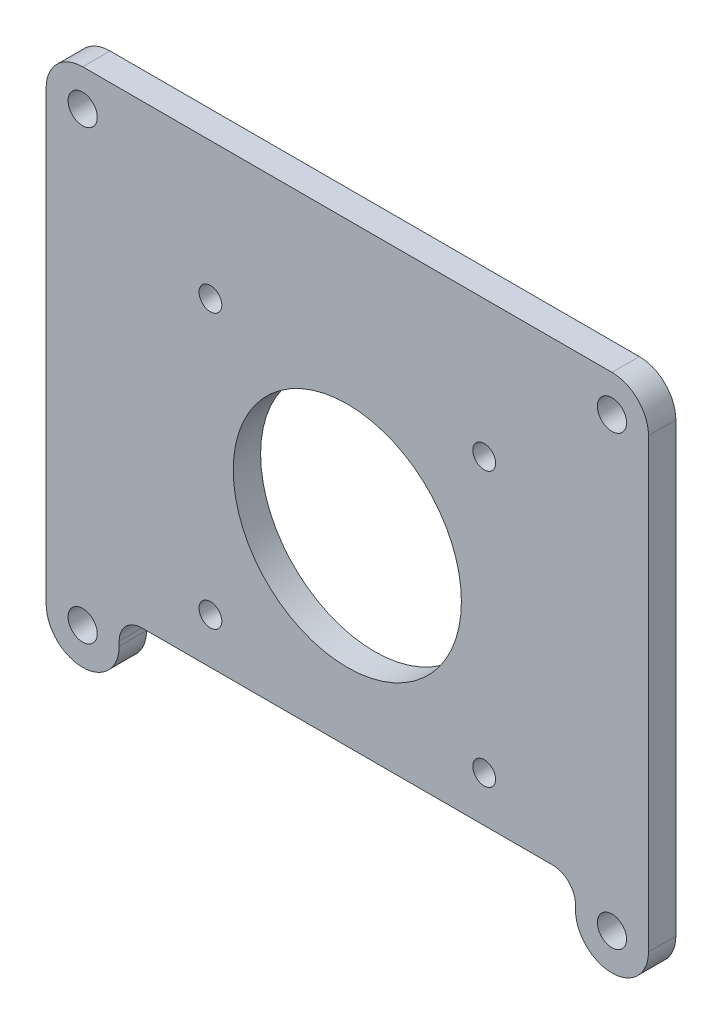
SolidWorks part; units mm, degrees
ref_plane "正面" through (0, 0, 0) normal (0, 0, 1) x (1, 0, 0)
ref_plane "平面" through (0, 0, 0) normal (0, 1, 0) x (1, 0, 0)
ref_plane "右側面" through (0, 0, 0) normal (1, 0, 0) x (0, 0, -1)
sketch "ｽｹｯﾁ1" plane through (0, 0, 0) normal (0, 0, 1) x (1, 0, 0)
  line L0 (22.5, 0) -> (-22.5, 0)
  line L1 (-25, -2.5) -> (-25, -3)
  line L2 (-33, -3) -> (-33, 46)
  line L3 (-29, 50) -> (29, 50)
  line L4 (0, 50) -> (0, 0) construction
  line L5 (-29, 46) -> (-29, -3) construction
  line L6 (33, -3) -> (33, 46)
  line L7 (25, -2.5) -> (25, -3)
  arc A0 (-33, -3) -> (-25, -3) centre (-29, -3) ccw
  arc A1 (-29, 50) -> (-33, 46) centre (-29, 46) ccw
  arc A2 (-25, -2.5) -> (-22.5, 0) centre (-22.5, -2.5) cw
  circle A3 centre (-29, -3) radius 1.6
  circle A4 centre (-29, 46) radius 1.6
  circle A5 centre (29, 46) radius 1.6
  circle A6 centre (29, -3) radius 1.6
  arc A7 (25, -2.5) -> (22.5, 0) centre (22.5, -2.5) ccw
  arc A8 (29, 50) -> (33, 46) centre (29, 46) cw
  arc A9 (33, -3) -> (25, -3) centre (29, -3) cw
  dimension "D1" = 49
  dimension "D3" = 2.5
  dimension "D4" = 3.2
  dimension "D5" = 4
  dimension "D2" = 29
  dimension "D6" = 3
extrude "ﾎﾞｽ - 押し出し1" add sketch "ｽｹｯﾁ1" along normal blind 3
sketch "ｽｹｯﾁ2" plane through (0, 0, 3) normal (0, 0, 1) x (1, 0, 0)
  line L0 (0, 20) -> (0, 0) construction
  line L1 (-15, 35) -> (15, 35) construction
  line L2 (-15, 35) -> (-15, 5) construction
  line L3 (-15, 5) -> (15, 5) construction
  line L4 (15, 35) -> (15, 5) construction
  line L5 (-15, 35) -> (15, 5) construction
  line L6 (-15, 5) -> (15, 35) construction
  circle A0 centre (-15, 35) radius 1.25
  circle A1 centre (-15, 5) radius 1.25
  circle A2 centre (15, 5) radius 1.25
  circle A3 centre (15, 35) radius 1.25
  circle A4 centre (0, 20) radius 12.5
  point P0 (0, 20)
  dimension "D1" = 2.5
  dimension "D3" = 25
  dimension "D2" = 30
  dimension "D4" = 20
extrude "ｶｯﾄ - 押し出し1" cut sketch "ｽｹｯﾁ2" against normal through all
